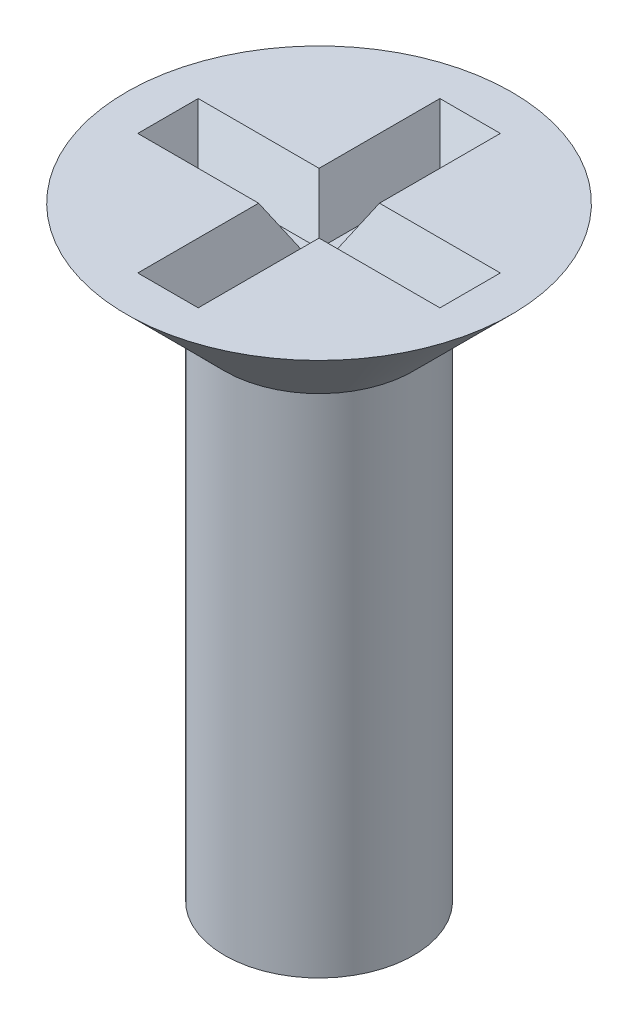
SolidWorks part; units mm, degrees
ref_plane "Спереди" through (0, 0, 0) normal (0, 0, 1) x (1, 0, 0)
ref_plane "Сверху" through (0, 0, 0) normal (0, 1, 0) x (1, 0, 0)
ref_plane "Справа" through (0, 0, 0) normal (1, 0, 0) x (0, 0, -1)
sketch "Эскиз1" plane through (0, 0, 0) normal (0, 0, 1) x (1, 0, 0)
  line L0 (0, 8) -> (-2.55, 8)
  line L1 (-2.55, 8) -> (-1.25, 6.7)
  line L2 (-1.25, 6.7) -> (-1.25, 0)
  line L3 (-1.25, 0) -> (0, 0)
  line L4 (0, 0) -> (0, 8)
  dimension "D1" = 1.25
  dimension "D2" = 2.55
  dimension "D3" = 45
  dimension "D4" = 8
revolve "Повернуть1" add sketch "Эскиз1" angle 360 about L4
sketch "Эскиз2" plane through (0, 8, 0) normal (0, 1, 0) x (1, 0, 0)
  line L0 (0.4, 0.4) -> (2, 0.4)
  line L1 (-0.4, -2) -> (0.4, -2)
  line L2 (-0.4, -2) -> (-0.4, -0.4)
  line L3 (-0.4, 2) -> (0.4, 2)
  line L4 (0.4, -2) -> (0.4, -0.4)
  line L5 (-0.4, 0.4) -> (-0.4, 2)
  line L6 (0.4, -0.4) -> (2, -0.4)
  line L7 (-2, -0.4) -> (-0.4, -0.4)
  line L8 (-2, -0.4) -> (-2, 0.4)
  line L9 (-2, 0.4) -> (-0.4, 0.4)
  line L10 (2, -0.4) -> (2, 0.4)
  line L11 (0.4, 0.4) -> (0.4, 2)
  line L12 (-0.4, 0.4) -> (0.4, -0.4) construction
  line L13 (-0.4, -0.4) -> (0.4, 0.4) construction
  point P0 (0, 0)
  point P6 (0, 0)
  point P15 (0, 0)
  dimension "D1" = 4
  dimension "D2" = 0.8
extrude "Вырез-Вытянуть1" cut sketch "Эскиз2" against normal blind 0.6 draft 28
